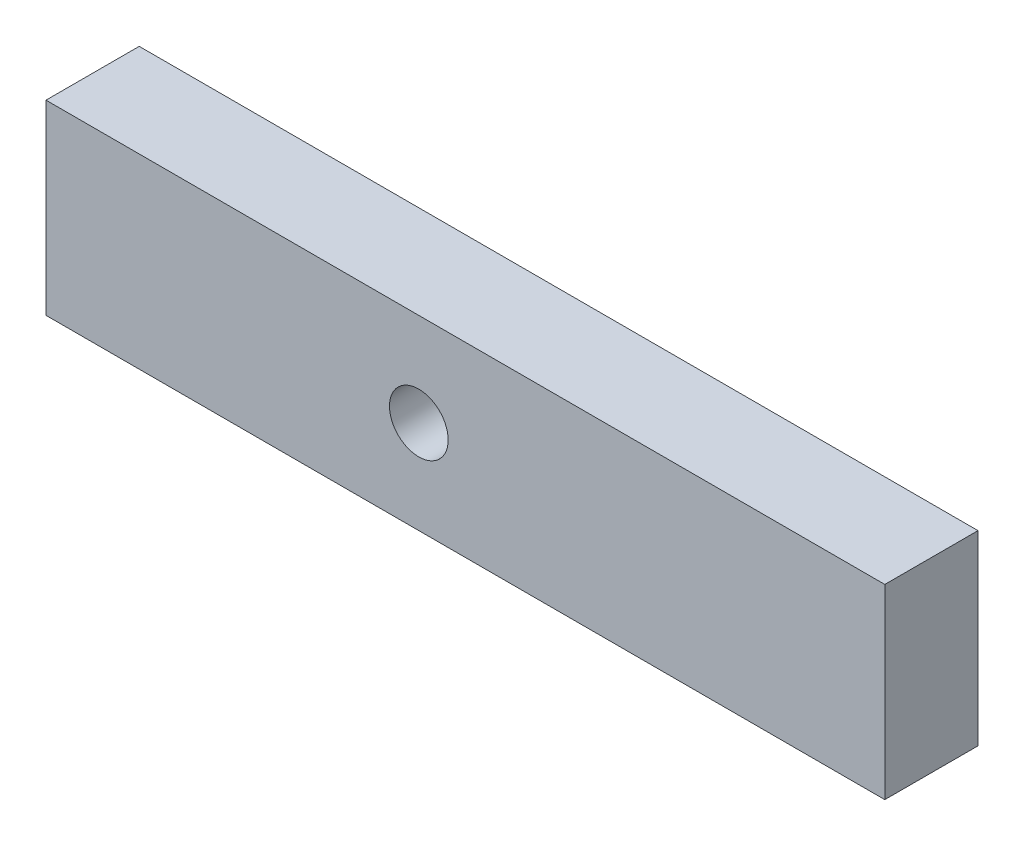
SolidWorks part; units mm, degrees
ref_plane "Front Plane" through (0, 0, 0) normal (0, 0, 1) x (1, 0, 0)
ref_plane "Top Plane" through (0, 0, 0) normal (0, 1, 0) x (1, 0, 0)
ref_plane "Right Plane" through (0, 0, 0) normal (1, 0, 0) x (0, 0, -1)
sketch "Sketch1" plane through (0, 0, 0) normal (0, 0, 1) x (1, 0, 0)
  line L1 (0, 0) -> (114.3, 0)
  line L2 (0, 0) -> (0, 25.4)
  line L3 (0, 25.4) -> (114.3, 25.4)
  line L4 (114.3, 0) -> (114.3, 25.4)
  circle A0 centre (50.8, 12.7) radius 4
  dimension "D3" = 8
  dimension "D1" = 114.3
  dimension "D2" = 25.4
extrude "Boss-Extrude1" add sketch "Sketch1" along normal blind 12.7
